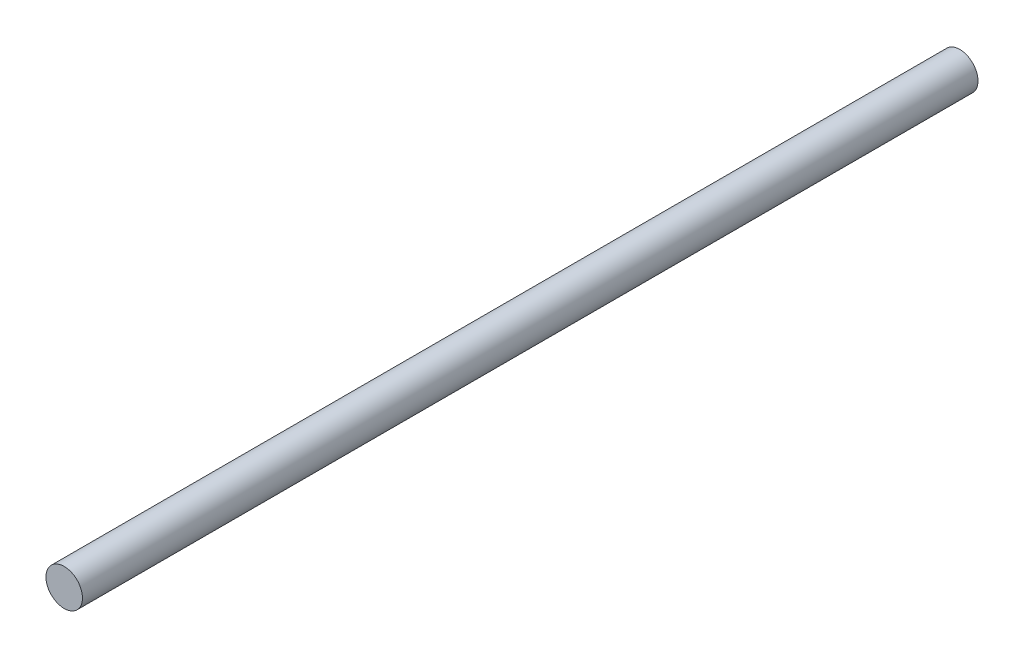
SolidWorks part; units mm, degrees
material "СТ3КП"
ref_plane "Спереди" through (0, 0, 0) normal (0, 0, 1) x (1, 0, 0)
ref_plane "Сверху" through (0, 0, 0) normal (0, 1, 0) x (1, 0, 0)
ref_plane "Справа" through (0, 0, 0) normal (1, 0, 0) x (0, 0, -1)
sketch "Эскиз1" plane through (0, 0, 0) normal (0, 0, 1) x (1, 0, 0)
  circle A0 centre (0, 0) radius 6 construction
  circle A1 centre (0, 0) radius 6
extrude "Бобышка-Вытянуть1" add sketch "Эскиз1" along normal up to surface (147.3 mm away)
mirror "Зеркальное отражение1" about plane through (0, 0, 0) normal (0, 0, 1) of bodies 103
